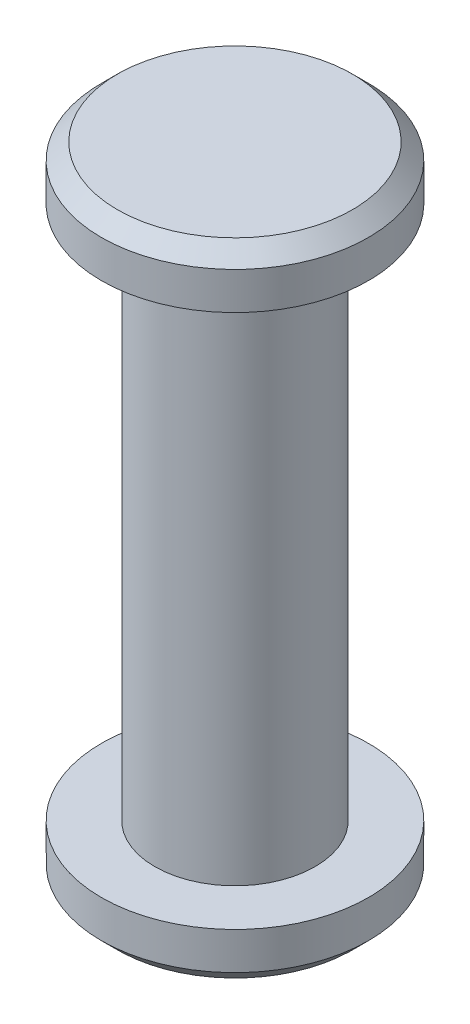
SolidWorks part; units mm, degrees
ref_plane "Front Plane" through (0, 0, 0) normal (0, 0, 1) x (1, 0, 0)
ref_plane "Top Plane" through (0, 0, 0) normal (0, 1, 0) x (1, 0, 0)
ref_plane "Right Plane" through (0, 0, 0) normal (1, 0, 0) x (0, 0, -1)
sketch "Sketch2" plane through (0, 0, 0) normal (0, 0, 1) x (1, 0, 0)
  line L0 (0, 100.2834) -> (0, -125.9902) construction
  line L1 (0, 60) -> (-25, 60)
  line L2 (-25, 60) -> (-25, 50)
  line L3 (-25, 50) -> (-15, 50)
  line L4 (-15, 50) -> (-15, -50)
  line L6 (0, 0) -> (0, 60)
  line L7 (-25, -50) -> (-15, -50)
  line L8 (-25, -60) -> (-25, -50)
  line L9 (0, -60) -> (-25, -60)
  line L10 (0, 0) -> (0, -60)
  point P5 (0, 30)
  dimension "D1" = 15
  dimension "D2" = 25
  dimension "D3" = 10
  dimension "D4" = 100
revolve "Revolve1" add sketch "Sketch2" angle 360 about L0
chamfer "Chamfer1" distance 3 angle 45 2 edges at (0, 60, 25) (0, -60, 25)
